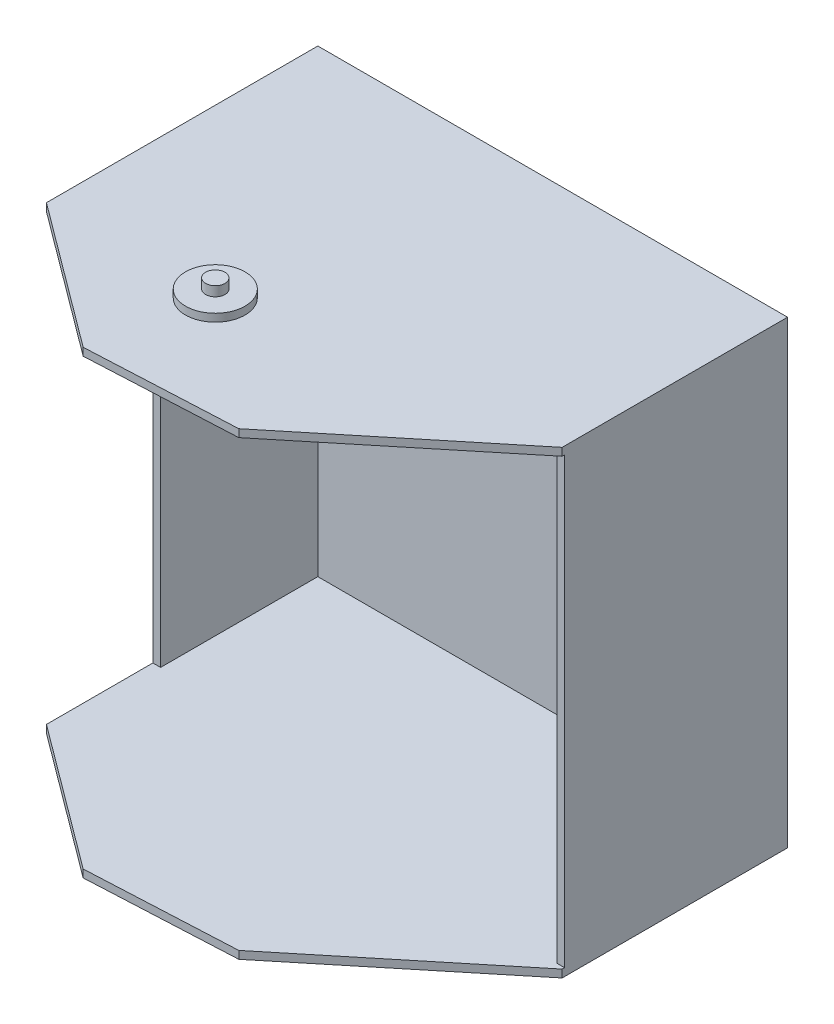
SolidWorks part; units mm, degrees
ref_plane "Front Plane" through (0, 0, 0) normal (0, 0, 1) x (1, 0, 0)
ref_plane "Top Plane" through (0, 0, 0) normal (0, 1, 0) x (1, 0, 0)
ref_plane "Right Plane" through (0, 0, 0) normal (1, 0, 0) x (0, 0, -1)
sketch "Sketch1" plane through (0, 0, 0) normal (0, 1, 0) x (1, 0, 0)
  line L0 (-71.1993, 0) -> (119.8007, 0)
  line L1 (119.8007, 0) -> (119.8007, -90)
  line L2 (119.8007, -90) -> (46.2729, -150.1553)
  line L3 (46.2729, -150.1553) -> (-15.0357, -153.1811)
  line L4 (-15.0357, -153.1811) -> (-74.3993, -109)
  line L5 (-74.3993, -109) -> (-74.3993, -65)
  line L6 (-74.3993, -65) -> (-71.1993, -65)
  line L7 (-71.1993, -65) -> (-71.1993, 0)
  dimension "D1" = 191
  dimension "D2" = 90
  dimension "D3" = 74
  dimension "D4" = 95
  dimension "D6" = 65
  dimension "D7" = 3.2
  dimension "D9" = 44
extrude "Boss-Extrude1" add sketch "Sketch1" along normal blind 3.2
sketch "Sketch3" plane through (0, 0, 0) normal (0, -1, 0) x (1, 0, 0)
  line L1 (-74.3993, 108.0683) -> (119.7657, 108.4369) construction
  line L2 (-74.3993, 65) -> (-74.3993, 109) construction
  line L3 (-5.3993, 152.7055) -> (-5.3993, 0) construction
  line L4 (-15.0357, 153.1811) -> (46.2729, 150.1553) construction
  line L5 (119.8007, 0) -> (-71.1993, 0) construction
  circle A0 centre (-5.3993, 108.1993) radius 12.3
  dimension "D3" = 24.6
  dimension "D1" = 45
  dimension "D2" = 69
extrude "Boss-Extrude2" add sketch "Sketch3" along normal blind 3.2
sketch "Sketch4" plane through (0, -3.2, 0) normal (0, -1, 0) x (1, 0, 0)
  circle A0 centre (-5.3993, 108.1993) radius 4
  dimension "D1" = 8
extrude "Boss-Extrude3" add sketch "Sketch4" along normal blind 4
sketch "Sketch6" plane through (0, 0, 0) normal (0, 1, 0) x (1, 0, 0)
  line L0 (-74.3993, -65) -> (-74.3993, 0)
  line L1 (-74.3993, 0) -> (-71.1993, 0)
  line L2 (-71.1993, 0) -> (-71.1993, -65)
  line L3 (-71.1993, -65) -> (-74.3993, -65)
extrude "Boss-Extrude4" add sketch "Sketch6" along normal blind 190
sketch "Sketch8" plane through (0, 0, 0) normal (0, 1, 0) x (1, 0, 0)
  line L0 (119.8007, 0) -> (116.6007, 0)
  line L1 (119.8007, 0) -> (-71.1993, 0) construction
  line L2 (116.6007, 0) -> (116.6007, -89)
  line L3 (116.6007, -89) -> (119.8007, -89)
  line L4 (119.8007, -90) -> (119.8007, 0) construction
  line L5 (119.8007, -89) -> (119.8007, 0)
  dimension "D1" = 3.2
  dimension "D2" = 89
extrude "Boss-Extrude5" add sketch "Sketch8" along normal blind 190
ref_plane "Plane2" through (0, 95, 0) normal (0, -1, 0) x (-1, 0, 0)
mirror "Mirror1" about plane through (0, 95, 0) normal (0, -1, 0) of "Boss-Extrude3", "Boss-Extrude1", "Boss-Extrude2"
sketch "Sketch9" plane through (0, 0, 0) normal (0, 0, 1) x (1, 0, 0)
  line L0 (22.7007, 190) -> (22.7007, 0) construction
  line L3 (-74.3993, 95) -> (119.8007, 95) construction
  line L4 (-74.3993, 186.8) -> (-74.3993, 3.2) construction
  line L5 (119.8007, 186.8) -> (119.8007, 3.2) construction
  line L6 (119.8007, 190) -> (-74.3993, 190) construction
  line L7 (119.8007, 0) -> (-74.3993, 0) construction
  line L8 (119.8007, 190) -> (119.8007, 0) construction
  line L9 (-74.3993, 0) -> (119.8007, 0)
  line L10 (-74.3993, 0) -> (-74.3993, 190)
  line L11 (-74.3993, 190) -> (119.8007, 190)
  line L12 (119.8007, 0) -> (119.8007, 190)
  line L13 (-74.3993, 0) -> (119.8007, 190) construction
  line L14 (-74.3993, 190) -> (119.8007, 0) construction
  point P12 (22.7007, 95)
extrude "Boss-Extrude7" add sketch "Sketch9" against normal blind 3.2
sketch "Sketch10" plane through (0, 3.2, 0) normal (0, 1, 0) x (1, 0, 0)
  line L0 (22.7007, 3.2) -> (22.7007, -151.3187) construction
  line L1 (119.8007, 3.2) -> (-74.3993, 3.2) construction
  line L2 (-15.0357, -153.1811) -> (46.2729, -150.1553) construction
